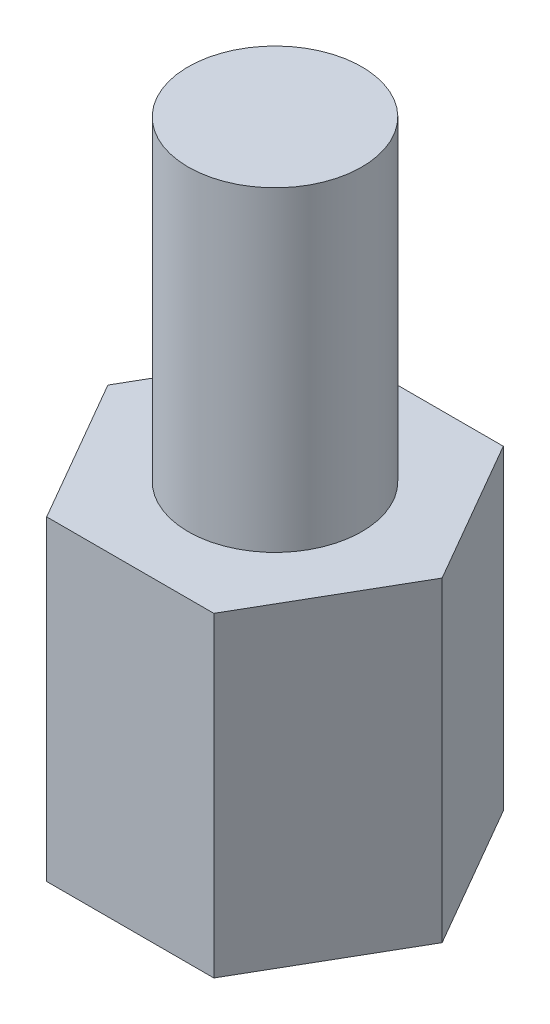
SolidWorks part; units mm, degrees
ref_plane "Front Plane" through (0, 0, 0) normal (0, 0, 1) x (1, 0, 0)
ref_plane "Top Plane" through (0, 0, 0) normal (0, 1, 0) x (1, 0, 0)
ref_plane "Right Plane" through (0, 0, 0) normal (1, 0, 0) x (0, 0, -1)
sketch "Sketch1" plane through (0, 0, 0) normal (0, 1, 0) x (1, 0, 0)
  line L1 (1.5877, 2.75) -> (-1.5877, 2.75)
  line L2 (-1.5877, 2.75) -> (-3.1754, 0)
  line L3 (-3.1754, 0) -> (-1.5877, -2.75)
  line L4 (-1.5877, -2.75) -> (1.5877, -2.75)
  line L5 (1.5877, -2.75) -> (3.1754, 0)
  line L6 (3.1754, 0) -> (1.5877, 2.75)
  circle A0 centre (0, 0) radius 1.5
  circle A1 centre (0, 0) radius 2.75 construction
  point P2 (0, 0)
  dimension "D1" = 5.5
  dimension "D2" = 3
extrude "Boss-Extrude1" add sketch "Sketch1" along normal blind 6
sketch "Sketch2" plane through (0, 6, 0) normal (0, 1, 0) x (1, 0, 0)
  circle A0 centre (0, 0) radius 1.65
  dimension "D1" = 3.3
extrude "Boss-Extrude2" add sketch "Sketch2" along normal blind 6
